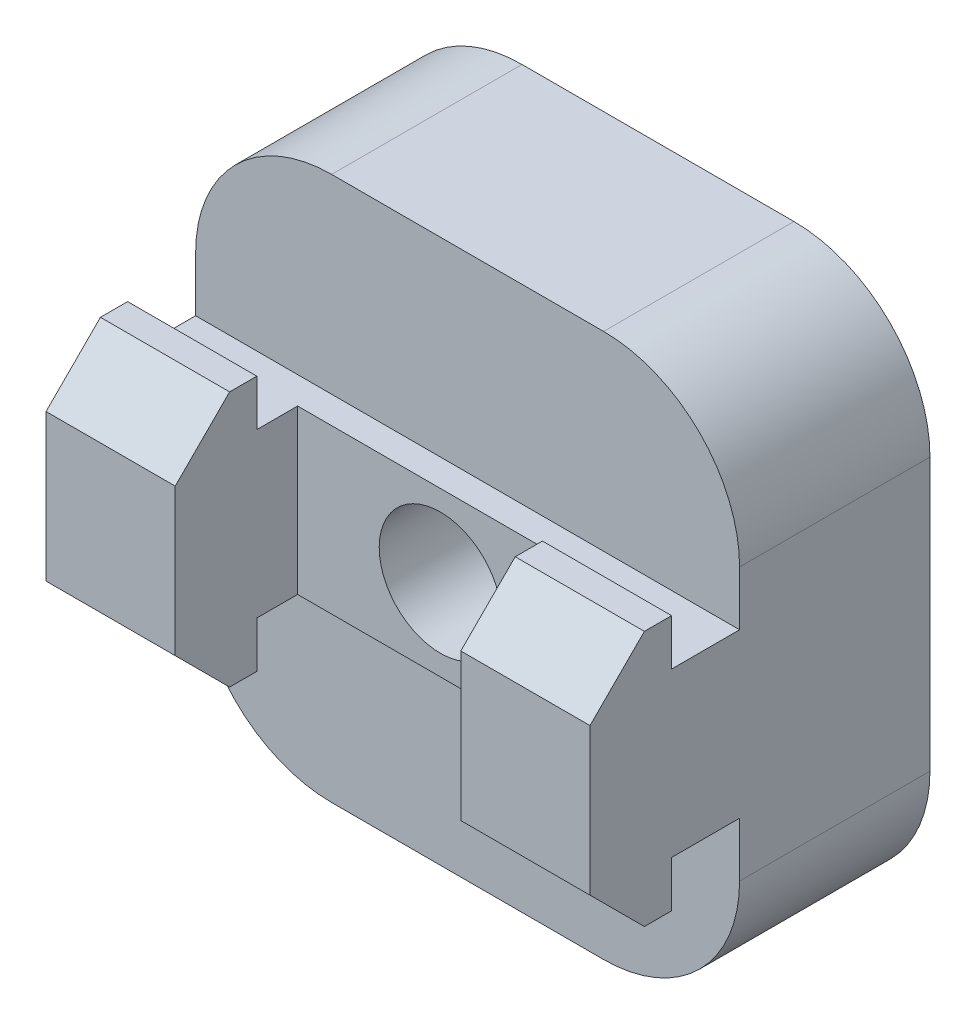
SolidWorks part; units mm, degrees
ref_plane "Front Plane" through (0, 0, 0) normal (0, 0, 1) x (1, 0, 0)
ref_plane "Top Plane" through (0, 0, 0) normal (0, 1, 0) x (1, 0, 0)
ref_plane "Right Plane" through (0, 0, 0) normal (1, 0, 0) x (0, 0, -1)
sketch "Sketch1" plane through (0, 0, 0) normal (1, 0, 0) x (0, 0, -1)
  line L2 (-9.5, 3) -> (-9.5, 4.7)
  line L3 (-9.5, 4.7) -> (-10.5, 4.7)
  line L4 (-10.5, 4.7) -> (-12.5, 2.7)
  line L5 (-12.5, 2.7) -> (-12.5, -2.7)
  line L6 (55, 0) -> (-55, 0) construction
  line L8 (0, -10) -> (0, 10)
  line L9 (0, 10) -> (-7, 10)
  line L10 (-7, 10) -> (-7, 3)
  line L12 (-9.5, 3) -> (-7, 3)
  line L13 (-9.5, -3) -> (-9.5, -4.7)
  line L14 (-9.5, -4.7) -> (-10.5, -4.7)
  line L15 (-10.5, -4.7) -> (-12.5, -2.7)
  line L16 (0, -10) -> (-7, -10)
  line L17 (-7, -10) -> (-7, -3)
  line L18 (-9.5, -3) -> (-7, -3)
  line L19 (0, 44.2539) -> (0, -44.2539) construction
  point P12 (-12.5, 3.2931)
  dimension "D1" = 2.5
  dimension "D2" = 4.7
  dimension "D3" = 10
  dimension "D4" = 3
  dimension "D5" = 3
  dimension "D6" = 1
  dimension "D7" = 2.7
  dimension "D8" = 7
extrude "Boss-Extrude1" add sketch "Sketch1" along normal mid plane 20
sketch "Sketch3" plane through (0, 0, 0) normal (0, 0, -1) x (-1, 0, 0)
  circle A0 centre (0, 0) radius 2.25
  dimension "D1" = 4.5
extrude "Cut-Extrude1" cut sketch "Sketch3" against normal through all
sketch "Sketch4" plane through (0, 0, 0) normal (1, 0, 0) x (0, 0, -1)
  line L0 (55, 0) -> (-55, 0) construction
  line L1 (-17, -8.55) -> (-8, -8.55)
  line L2 (-17, -8.55) -> (-17, 8.55)
  line L3 (-17, 8.55) -> (-8, 8.55)
  line L4 (-8, -8.55) -> (-8, 8.55)
  line L5 (-17, -8.55) -> (-8, 8.55) construction
  line L6 (-17, 8.55) -> (-8, -8.55) construction
  line L7 (-12.5, 2.7) -> (-12.5, -2.7) construction
  point P0 (-12.5, 0)
  point P7 (0, 0)
  dimension "D1" = 9
extrude "Cut-Extrude2" cut sketch "Sketch4" against normal mid plane 10.5
fillet "Fillet1" radius 5 4 edges at (-10, 10, 3.5) (-10, -10, 3.5) (10, -10, 3.5) (10, 10, 3.5)
